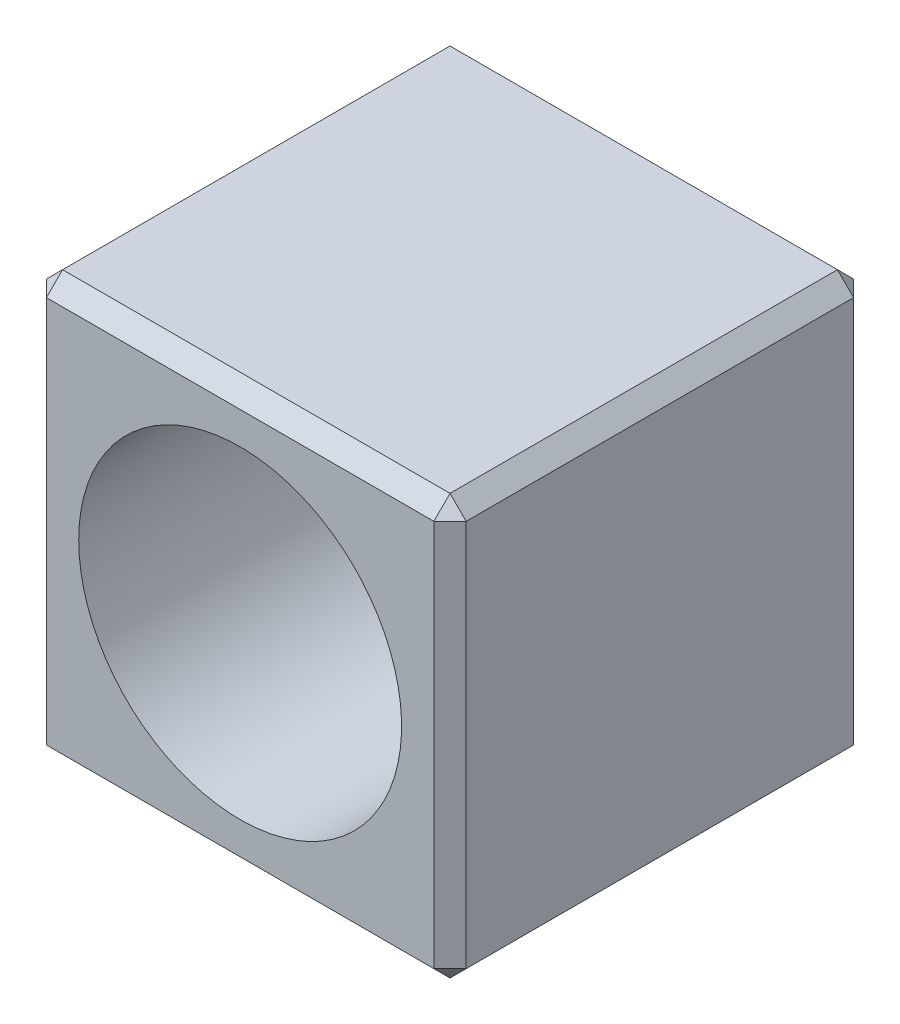
SolidWorks part; units mm, degrees
ref_plane "Front Plane" through (0, 0, 0) normal (0, 0, 1) x (1, 0, 0)
ref_plane "Top Plane" through (0, 0, 0) normal (0, 1, 0) x (1, 0, 0)
ref_plane "Right Plane" through (0, 0, 0) normal (1, 0, 0) x (0, 0, -1)
sketch "Sketch1" plane through (0, 0, 0) normal (0, 0, 1) x (1, 0, 0)
  line L1 (-6.5, 6.5) -> (6.5, 6.5)
  line L2 (-6.5, 6.5) -> (-6.5, -6.5)
  line L3 (-6.5, -6.5) -> (6.5, -6.5)
  line L4 (6.5, 6.5) -> (6.5, -6.5)
  line L5 (-6.5, 6.5) -> (6.5, -6.5) construction
  line L6 (-6.5, -6.5) -> (6.5, 6.5) construction
  circle A0 centre (0, 0) radius 5
  point P0 (0, 0)
  dimension "D1" = 10
  dimension "D2" = 13
  dimension "D3" = 13
extrude "Boss-Extrude1" add sketch "Sketch1" along normal blind 13
chamfer "Chamfer1" distance 0.5 angle 45 12 edges at (0, -6.5, 0) (0, 6.5, 0) (-6.5, 0, 0) (-6.5, -6.5, 6.5) (-6.5, 6.5, 6.5) (0, 6.5, 13) (-6.5, 0, 13) (0, -6.5, 13) (6.5, -6.5, 6.5) (6.5, 0, 0) (6.5, 6.5, 6.5) (6.5, 0, 13)
